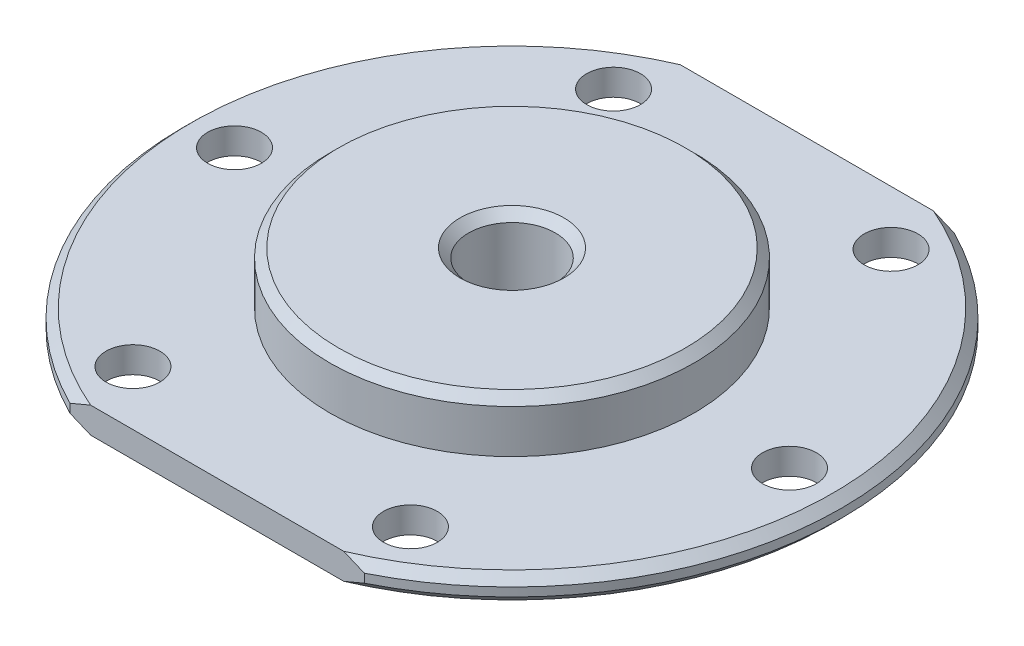
SolidWorks part; units mm, degrees
ref_plane "Front Plane" through (0, 0, 0) normal (0, 0, 1) x (1, 0, 0)
ref_plane "Top Plane" through (0, 0, 0) normal (0, 1, 0) x (1, 0, 0)
ref_plane "Right Plane" through (0, 0, 0) normal (1, 0, 0) x (0, 0, -1)
sketch "Sketch1" plane through (0, 0, 0) normal (0, 1, 0) x (1, 0, 0)
  line L0 (-8.4853, 17) -> (8.4853, 17)
  line L1 (-8.4853, -17) -> (8.4853, -17)
  arc A0 (-8.4853, 17) -> (-8.4853, -17) centre (0, 0) ccw
  circle A1 centre (0, 0) radius 16 construction
  arc A2 (8.4853, -17) -> (8.4853, 17) centre (0, 0) ccw
  circle A3 centre (-16, 0) radius 1.55
  circle A4 centre (-8, 13.8564) radius 1.55
  circle A5 centre (8, 13.8564) radius 1.55
  circle A6 centre (16, 0) radius 1.55
  circle A7 centre (8, -13.8564) radius 1.55
  circle A8 centre (-8, -13.8564) radius 1.55
  point P21 (0, 0)
  dimension "D1" = 38
  dimension "D2" = 32
  dimension "D5" = 3.1
  dimension "D3" = 17
  dimension "D4" = 17
  dimension "D6" = 6
extrude "Boss-Extrude1" add sketch "Sketch1" along normal blind 1.5
sketch "Sketch2" plane through (0, 1.5, 0) normal (0, 1, 0) x (1, 0, 0)
  circle A0 centre (0, 0) radius 10.5
extrude "Boss-Extrude2" add sketch "Sketch2" along normal blind 3
sketch "Sketch3" plane through (0, 0, 0) normal (0, -1, 0) x (1, 0, 0)
  circle A0 centre (0, 0) radius 5
extrude "Boss-Extrude3" add sketch "Sketch3" along normal blind 5
sketch "Sketch4" plane through (0, 4.5, 0) normal (0, 1, 0) x (1, 0, 0)
  circle A0 centre (0, 0) radius 2.5
extrude "Cut-Extrude1" cut sketch "Sketch4" against normal through all
chamfer "Chamfer1" distance 0.5 angle 45 8 edges at (0, -5, 2.5) (0, -5, -5) (0, 4.5, 2.5) (0, 4.5, 10.5) (19, 0, 0) (19, 1.5, 0) (-19, 0, 0) (-19, 1.5, 0)
